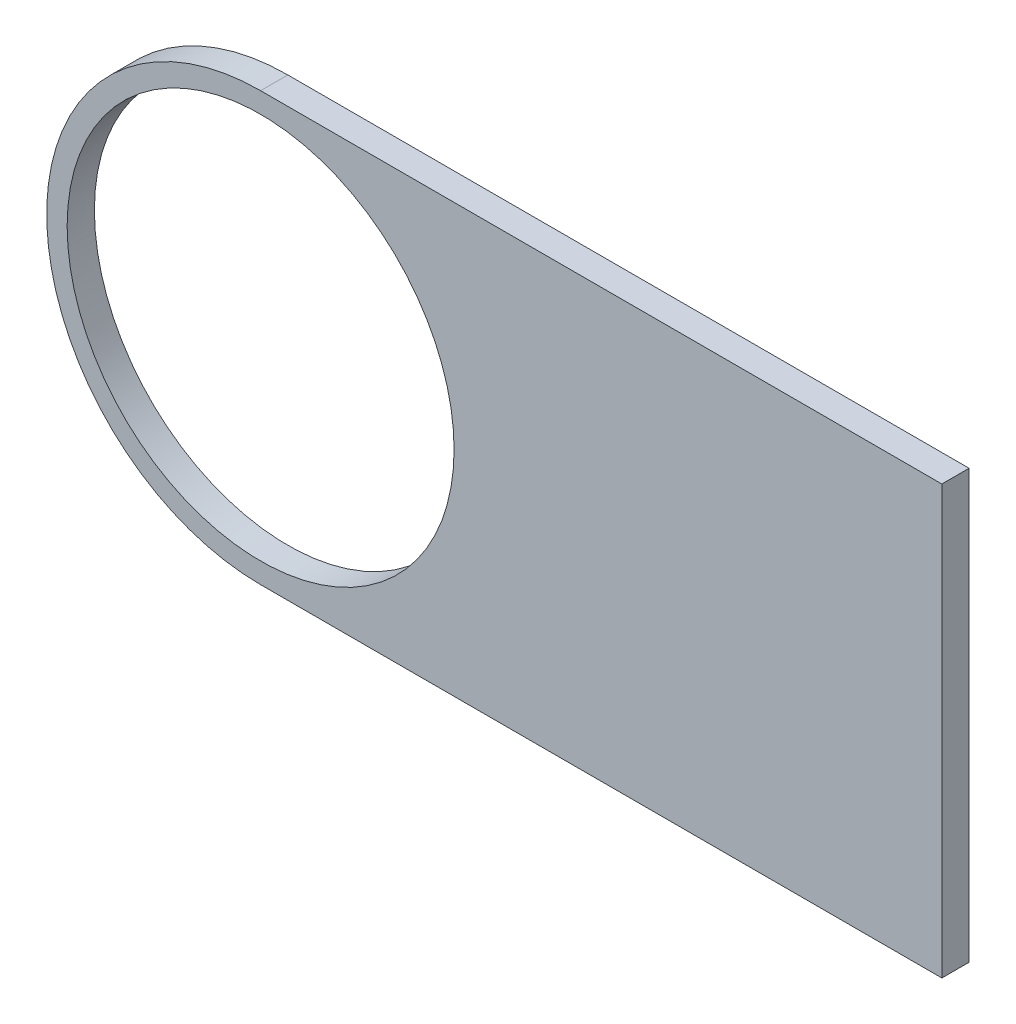
SolidWorks part; units mm, degrees
ref_plane "Front Plane" through (0, 0, 0) normal (0, 0, 1) x (1, 0, 0)
ref_plane "Top Plane" through (0, 0, 0) normal (0, 1, 0) x (1, 0, 0)
ref_plane "Right Plane" through (0, 0, 0) normal (1, 0, 0) x (0, 0, -1)
sketch "Sketch1" plane through (0, 0, 0) normal (0, 0, 1) x (1, 0, 0)
  circle A0 centre (0, 0) radius 19.939
  dimension "D1" = 39.878
extrude "Boss-Extrude1" add sketch "Sketch1" along normal blind 2.54
sketch "Sketch3" plane through (0, 0, 0) normal (1, 0, 0) x (0, 0, -1)
  line L0 (0, 21.9329) -> (0, -21.9329) construction
  line L1 (-2.54, 19.939) -> (0, 19.939)
  line L2 (-2.54, 19.939) -> (-2.54, -19.939)
  line L3 (-2.54, -19.939) -> (0, -19.939)
  line L4 (0, 19.939) -> (0, -19.939)
  line L5 (-2.54, -19.939) -> (0, -19.939) construction
  point P9 (0, 19.939)
extrude "Boss-Extrude2" add sketch "Sketch3" along normal blind 63.5
sketch "Sketch2" plane through (0, 0, 2.54) normal (0, 0, 1) x (1, 0, 0)
  circle A0 centre (0, 0) radius 18.034
  dimension "D1" = 36.068
extrude "Cut-Extrude1" cut sketch "Sketch2" against normal blind 2.54
